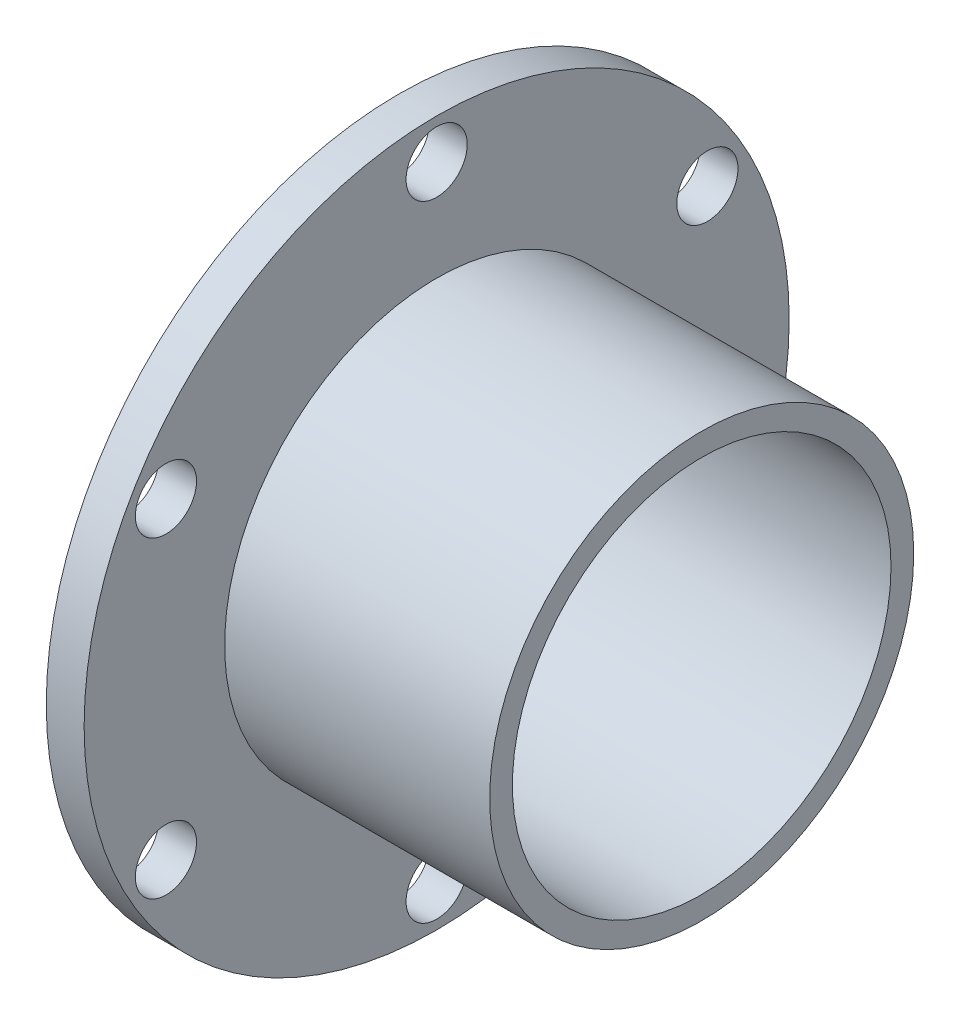
SolidWorks part; units mm, degrees
material "6061-T6 (SS)"
ref_plane "Front Plane" through (0, 0, 0) normal (0, 0, 1) x (1, 0, 0)
ref_plane "Top Plane" through (0, 0, 0) normal (0, 1, 0) x (1, 0, 0)
ref_plane "Right Plane" through (0, 0, 0) normal (1, 0, 0) x (0, 0, -1)
sketch "Sketch1" plane through (0, 0, 0) normal (1, 0, 0) x (0, 0, -1)
  line L0 (0, 0) -> (0, 20.64) construction
  arc A0 (-1.6237, 23.2194) -> (1.6237, -23.2194) centre (0, 0) ccw construction
  arc A1 (1.0588, 18.9205) -> (-1.0588, 22.3595) centre (0, 20.64) ccw construction
  circle A2 centre (0, 0) radius 23.2761
  circle A3 centre (0, 20.64) radius 2.0193
  circle A4 centre (17.8748, 10.32) radius 2.0193
  circle A5 centre (17.8748, -10.32) radius 2.0193
  circle A6 centre (0, -20.64) radius 2.0193
  circle A7 centre (-17.8748, -10.32) radius 2.0193
  circle A8 centre (-17.8748, 10.32) radius 2.0193
  circle A9 centre (0, 0) radius 17.46 construction
  point P21 (0, 0)
  dimension "D1" = 23.2761
  dimension "D2" = 2.0193
  dimension "D3" = 20.64
  dimension "D5" = 34.92
  dimension "D4" = 6
extrude "Boss-Extrude1" add sketch "Sketch1" along normal blind 2.5
sketch "Sketch4" plane through (0, 0, 0) normal (-1, 0, 0) x (0, 0, 1)
  circle A1 centre (0, 0) radius 14
  point P1 (0, 0)
  dimension "D1" = 28
extrude "Cut-Extrude2" cut sketch "Sketch4" against normal blind 30.8125
sketch "Sketch5" plane through (0, 0, 0) normal (1, 0, 0) x (0, 0, -1)
  circle A0 centre (0, 0) radius 12.5
  circle A1 centre (0, 0) radius 14
  circle A2 centre (0, 0) radius 14 construction
  dimension "D1" = 25
extrude "Boss-Extrude2" add sketch "Sketch5" along normal blind 20
